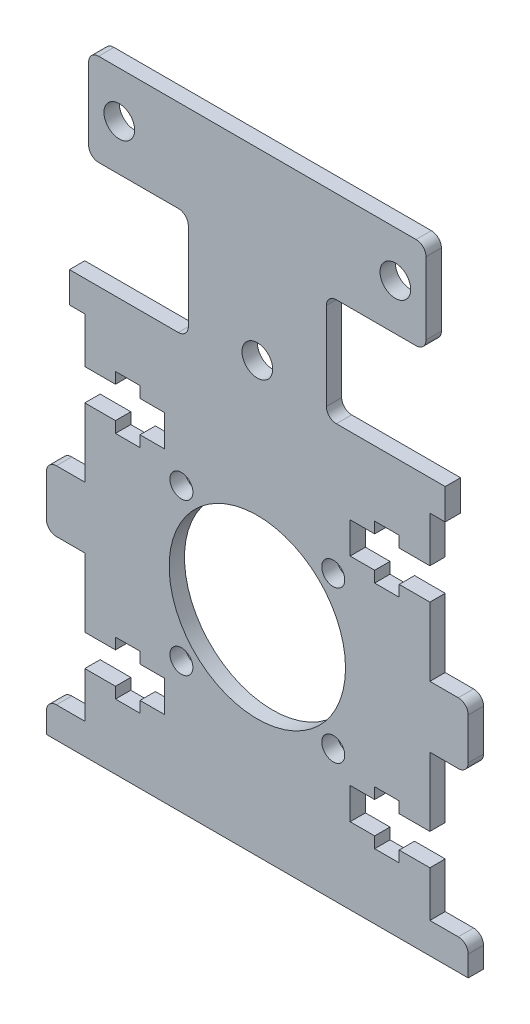
SolidWorks part; units mm, degrees
ref_plane "前视基准面" through (0, 0, 0) normal (0, 0, 1) x (1, 0, 0)
ref_plane "上视基准面" through (0, 0, 0) normal (0, 1, 0) x (1, 0, 0)
ref_plane "右视基准面" through (0, 0, 0) normal (1, 0, 0) x (0, 0, -1)
sketch "草图1" plane through (0, 0, 0) normal (0, 0, 1) x (1, 0, 0)
  line L0 (-22.5, 0) -> (-24.9483, 0) construction
  line L1 (22.5, -27) -> (-22.5, -27)
  line L3 (22.5, 27) -> (-22.5, 27) construction
  line L4 (-22.5, -27) -> (-22.5, 27) construction
  line L5 (22.5, -27) -> (-22.5, 27) construction
  line L6 (22.5, 27) -> (-22.5, -27) construction
  line L7 (-22.5, 4) -> (-27.5, 4)
  line L8 (-27.5, 4) -> (-27.5, -4)
  line L9 (-27.5, -4) -> (-22.5, -4)
  line L10 (-22.5, 17.05) -> (-18.5, 17.05)
  line L11 (-18.5, 17.05) -> (-18.5, 18.5)
  line L12 (-18.5, 18.5) -> (-15.3, 18.5)
  line L13 (-15.3, 18.5) -> (-15.3, 17.05)
  line L14 (-15.3, 17.05) -> (-12.1, 17.05)
  line L15 (-12.1, 17.05) -> (-12.1, 12.95)
  line L16 (-12.1, 12.95) -> (-15.3, 12.95)
  line L17 (-15.3, 12.95) -> (-15.3, 11.5)
  line L18 (-15.3, 11.5) -> (-18.5, 11.5)
  line L19 (-18.5, 11.5) -> (-18.5, 12.95)
  line L20 (-18.5, 12.95) -> (-22.5, 12.95)
  line L21 (-18.5, -12.95) -> (-22.5, -12.95)
  line L22 (-18.5, -11.5) -> (-18.5, -12.95)
  line L23 (-15.3, -11.5) -> (-18.5, -11.5)
  line L24 (-15.3, -12.95) -> (-15.3, -11.5)
  line L25 (-12.1, -12.95) -> (-15.3, -12.95)
  line L26 (-12.1, -17.05) -> (-12.1, -12.95)
  line L27 (-15.3, -17.05) -> (-12.1, -17.05)
  line L28 (-15.3, -18.5) -> (-15.3, -17.05)
  line L29 (-18.5, -18.5) -> (-15.3, -18.5)
  line L30 (-18.5, -17.05) -> (-18.5, -18.5)
  line L31 (-22.5, -17.05) -> (-18.5, -17.05)
  line L32 (-22.5, -23) -> (-27.5, -23)
  line L33 (-27.5, -23) -> (-27.5, -27)
  line L34 (-27.5, -27) -> (-22.5, -27)
  line L35 (-27.5, 23) -> (-27.5, 27)
  line L36 (-22.5, 23) -> (-27.5, 23)
  line L37 (-27.5, 27) -> (-22.5, 27)
  line L38 (0, 0) -> (0, -4) construction
  line L39 (22.5, -27) -> (22.5, 27) construction
  line L40 (22.5, 0) -> (24.9483, 0) construction
  line L41 (27.5, 27) -> (22.5, 27)
  line L42 (22.5, 23) -> (27.5, 23)
  line L43 (27.5, 23) -> (27.5, 27)
  line L44 (27.5, -27) -> (22.5, -27)
  line L45 (27.5, -23) -> (27.5, -27)
  line L46 (22.5, -23) -> (27.5, -23)
  line L47 (22.5, -17.05) -> (18.5, -17.05)
  line L48 (18.5, -17.05) -> (18.5, -18.5)
  line L49 (18.5, -18.5) -> (15.3, -18.5)
  line L50 (15.3, -18.5) -> (15.3, -17.05)
  line L51 (15.3, -17.05) -> (12.1, -17.05)
  line L52 (12.1, -17.05) -> (12.1, -12.95)
  line L53 (12.1, -12.95) -> (15.3, -12.95)
  line L54 (15.3, -12.95) -> (15.3, -11.5)
  line L55 (15.3, -11.5) -> (18.5, -11.5)
  line L56 (18.5, -11.5) -> (18.5, -12.95)
  line L57 (18.5, -12.95) -> (22.5, -12.95)
  line L58 (18.5, 12.95) -> (22.5, 12.95)
  line L59 (18.5, 11.5) -> (18.5, 12.95)
  line L60 (15.3, 11.5) -> (18.5, 11.5)
  line L61 (15.3, 12.95) -> (15.3, 11.5)
  line L62 (12.1, 12.95) -> (15.3, 12.95)
  line L63 (12.1, 17.05) -> (12.1, 12.95)
  line L64 (15.3, 17.05) -> (12.1, 17.05)
  line L65 (15.3, 18.5) -> (15.3, 17.05)
  line L66 (18.5, 18.5) -> (15.3, 18.5)
  line L67 (18.5, 17.05) -> (18.5, 18.5)
  line L68 (22.5, 17.05) -> (18.5, 17.05)
  line L69 (27.5, -4) -> (22.5, -4)
  line L70 (27.5, 4) -> (27.5, -4)
  line L71 (22.5, 4) -> (27.5, 4)
  line L72 (-22.5, 23) -> (-22.5, 17.05)
  line L73 (-22.5, 12.95) -> (-22.5, 4)
  line L74 (-22.5, -4) -> (-22.5, -12.95)
  line L75 (-22.5, -17.05) -> (-22.5, -23)
  line L76 (22.5, -23) -> (22.5, -17.05)
  line L77 (22.5, -12.95) -> (22.5, -4)
  line L78 (22.5, 4) -> (22.5, 12.95)
  line L79 (22.5, 23) -> (22.5, 17.05)
  line L80 (0, 0) -> (0, 47) construction
  line L81 (0, 47) -> (-18, 47) construction
  line L82 (22, 53) -> (-22, 53)
  line L83 (-22, 53) -> (-22, 41)
  line L84 (-22, 41) -> (-9, 41)
  line L85 (-9, 41) -> (-9, 27)
  line L86 (-9, 27) -> (-22.5, 27)
  line L87 (22, 53) -> (22, 41)
  line L88 (22, 41) -> (9, 41)
  line L89 (9, 41) -> (9, 27)
  line L90 (9, 27) -> (22.5, 27)
  line L91 (-12.1, 15) -> (-22.5, 15) construction
  circle A0 centre (0, 0) radius 14 construction
  circle A1 centre (9.8995, 9.8995) radius 1.5
  circle A5 centre (0, 0) radius 11.5
  circle A6 centre (9.8995, -9.8995) radius 1.5
  circle A7 centre (-9.8995, -9.8995) radius 1.5
  circle A8 centre (-9.8995, 9.8995) radius 1.5
  circle A9 centre (-18, 47) radius 2
  circle A10 centre (18, 47) radius 2
  circle A11 centre (0, 29) radius 2
  point P35 (-16.9, 11.5)
  point P48 (-21.5, -15)
  point P91 (21.5, -15)
  dimension "D2" = 23
  dimension "D12" = 3
  dimension "D17" = 28
  dimension "D21" = 18
  dimension "D22" = 18
  dimension "D27" = 4
  dimension "D3" = 45
  dimension "D4" = 54
  dimension "D5" = 8
  dimension "D6" = 5
  dimension "D7" = 4
  dimension "D8" = 15
  dimension "D9" = 3.2
  dimension "D10" = 4
  dimension "D11" = 4.1
  dimension "D13" = 7
  dimension "D14" = 4
  dimension "D15" = 5
  dimension "D19" = 29
  dimension "D20" = 18
  dimension "D23" = 13
  dimension "D24" = 12
  dimension "D25" = 6
  dimension "D26" = 4
  dimension "D18" = 4
extrude "凸台-拉伸1" add sketch "草图1" along normal blind 2
sketch "草图2" plane through (-22.5, 0, 0) normal (-1, 0, 0) x (0, 0, 1)
  line L0 (1, 17.05) -> (1, 12.95) construction
  line L1 (2, 17.05) -> (0, 17.05) construction
  line L2 (2, 12.95) -> (0, 12.95) construction
  line L3 (-0.15, 27.15) -> (4.15, 27.15) construction
  line L4 (4.15, -4.15) -> (-0.15, -4.15)
  line L5 (4.15, -4.15) -> (4.15, 4.15)
  line L6 (4.15, 4.15) -> (-0.15, 4.15)
  line L7 (-0.15, -4.15) -> (-0.15, 4.15)
  line L8 (4.15, -4.15) -> (-0.15, 4.15) construction
  line L9 (4.15, 4.15) -> (-0.15, -4.15) construction
  line L18 (4.15, 27.15) -> (4.15, 22.85)
  line L19 (-0.15, 22.85) -> (4.15, 22.85)
  line L20 (-0.15, 27.15) -> (-0.15, 22.85)
  line L21 (2, 0) -> (2.8697, 0) construction
  line L22 (-0.15, -27.15) -> (4.15, -27.15) construction
  line L23 (1, -17.05) -> (1, -12.95) construction
  line L24 (-0.15, -27.15) -> (-0.15, -22.85)
  line L25 (-0.15, -22.85) -> (4.15, -22.85)
  line L26 (4.15, -27.15) -> (4.15, -22.85)
  line L27 (4.15, -27.15) -> (8, -27.15)
  line L28 (8, -27.15) -> (8, 27.15)
  line L29 (8, 27.15) -> (4.15, 27.15)
  line L30 (-0.15, -27.15) -> (-64.002, -27.15)
  line L31 (-64.002, -27.15) -> (-64.002, 27.15)
  line L32 (-64.002, 27.15) -> (-0.15, 27.15)
  circle A0 centre (1, 15) radius 2.05
  circle A1 centre (1, -15) radius 2.05
  point P8 (2, 0)
  dimension "D1" = 8.3
  dimension "D2" = 4.3
sketch "草图3" plane through (22.5, 0, 0) normal (1, 0, 0) x (0, 0, -1)
  line L0 (-1, 12.95) -> (-1, 17.05)
  line L1 (-2, 12.95) -> (0, 12.95) construction
  line L2 (-2, 17.05) -> (0, 17.05) construction
  circle A0 centre (-1, 15) radius 2.05
fillet "圆角1" radius 1.3 16 edges at (-9, 27, 1) (9, 27, 1) (9, 41, 1) (-9, 41, 1) (22, 53, 1) (22, 41, 1) (-22, 53, 1) (-22, 41, 1) (-27.5, -23, 1) (-27.5, 23, 1) (-27.5, 4, 1) (-27.5, -4, 1) (27.5, -23, 1) (27.5, 4, 1) (27.5, -4, 1) (27.5, 23, 1)
sketch "草图4" plane through (0, 0, 2) normal (0, 0, 1) x (1, 0, 0)
  line L11 (27.5, 27) -> (24.5, 27)
  line L12 (27.5, 27) -> (27.5, 21.1214)
  line L13 (27.5, 21.1214) -> (24.5, 21.1214)
  line L14 (24.5, 27) -> (24.5, 21.1214)
  line L15 (-27.5, 27) -> (-24.5, 27)
  line L16 (-27.5, 27) -> (-27.5, 15.6557)
  line L17 (-27.5, 15.6557) -> (-24.5, 15.6557)
  line L18 (-24.5, 27) -> (-24.5, 15.6557)
extrude "切除-拉伸1" cut sketch "草图4" against normal blind 2
